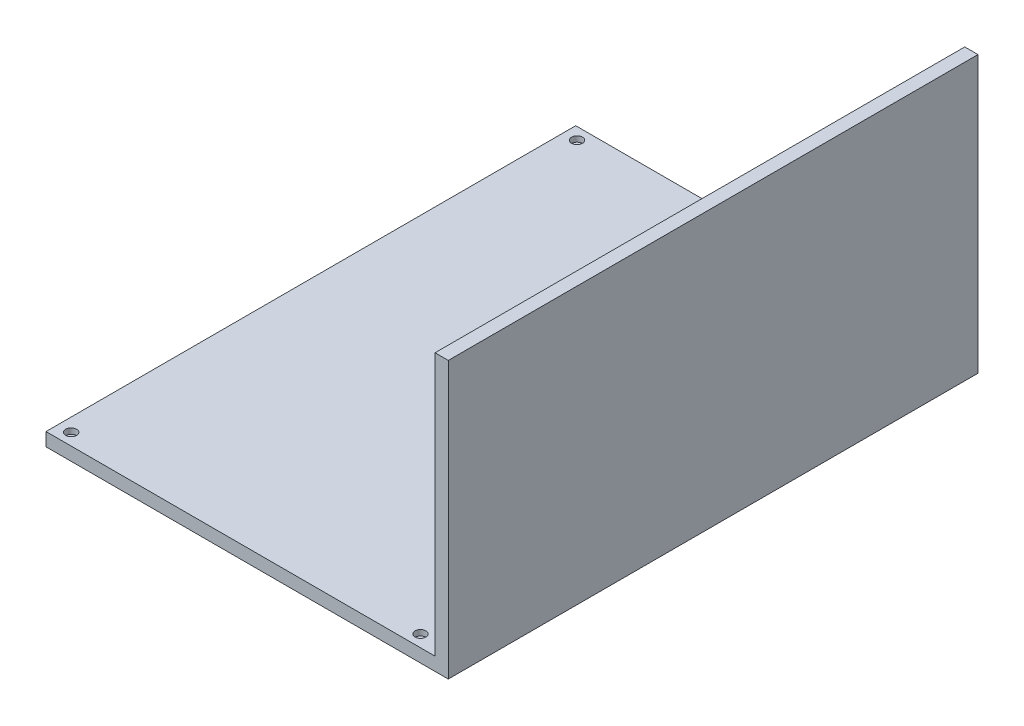
SolidWorks part; units mm, degrees
ref_plane "Front Plane" through (0, 0, 0) normal (0, 0, 1) x (1, 0, 0)
ref_plane "Top Plane" through (0, 0, 0) normal (0, 1, 0) x (1, 0, 0)
ref_plane "Right Plane" through (0, 0, 0) normal (1, 0, 0) x (0, 0, -1)
sketch "Croquis2" plane through (0, 0, 0) normal (0, 0, 1) x (1, 0, 0)
  line L0 (0, 0) -> (146.881, 0)
  line L1 (146.881, 0) -> (146.881, 99.2)
  line L2 (0, -5) -> (151.881, -5)
  line L3 (151.881, -5) -> (151.881, 99.2)
  line L4 (0, 0) -> (0, -5)
  line L5 (146.881, 99.2) -> (151.881, 99.2)
  dimension "D1" = 146.881
  dimension "D2" = 99.2
  dimension "D3" = 5
extrude "Saliente-Extruir1" add sketch "Croquis2" along normal blind 200
sketch "Croquis3" plane through (0, 0, 0) normal (0, 1, 0) x (1, 0, 0)
  line L0 (0, -100) -> (146.881, -100) construction
  line L1 (0, -200) -> (0, 0) construction
  line L2 (146.881, -200) -> (146.881, 0) construction
  line L3 (73.4405, 0) -> (73.4405, -200) construction
  line L4 (146.881, 0) -> (0, 0) construction
  line L5 (146.881, -200) -> (0, -200) construction
  line L7 (146.881, -200) -> (146.881, 0) construction
  circle A0 centre (5, -195.5) radius 2.05
  circle A1 centre (136.881, -195.5) radius 2.05
  circle A2 centre (136.881, -4.5) radius 2.05
  circle A3 centre (5, -4.5) radius 2.05
  point P14 (2.95, -195.5)
  point P15 (5, -197.55)
  point P18 (138.931, -195.5)
  point P21 (136.881, -197.55)
  point P28 (11.4714, -198.7756)
  dimension "D1" = 4.1
  dimension "D4" = 4.1
  dimension "D5" = 4.5
  dimension "D6" = 10
  dimension "D2" = 4.5
  dimension "D3" = 5
extrude "Cortar-Extruir1" cut sketch "Croquis3" against normal blind 2.1
sketch "Croquis4" plane through (146.881, 0, 0) normal (-1, 0, 0) x (0, 0, 1)
  line L0 (100, 99.2) -> (100, 0) construction
  line L1 (200, 99.2) -> (0, 99.2) construction
  line L2 (200, 0) -> (0, 0) construction
  line L3 (0, 99.2) -> (0, 0) construction
  circle A0 centre (4.5, 15) radius 2.05
  circle A1 centre (4.5, 94.7) radius 2.05
  circle A2 centre (195.5, 15) radius 2.05
  circle A3 centre (195.5, 94.7) radius 2.05
  point P10 (4.5, 12.95)
  point P11 (2.45, 15)
  point P12 (2.45, 94.7)
  point P13 (4.5, 96.75)
  dimension "D1" = 4.1
  dimension "D2" = 4.1
  dimension "D3" = 4.5
  dimension "D4" = 4.5
  dimension "D5" = 15
  dimension "D6" = 4.5
extrude "Cortar-Extruir2" cut sketch "Croquis4" against normal blind 2.1
